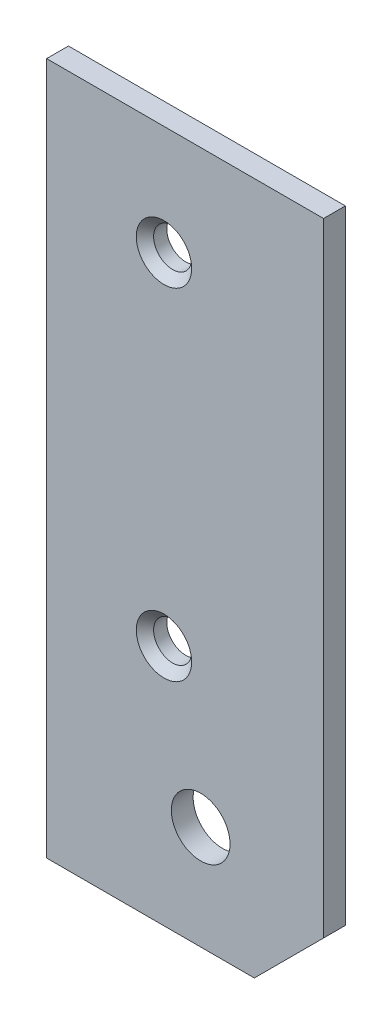
SolidWorks part; units mm, degrees
ref_plane "Front Plane" through (0, 0, 0) normal (0, 0, 1) x (1, 0, 0)
ref_plane "Top Plane" through (0, 0, 0) normal (0, 1, 0) x (1, 0, 0)
ref_plane "Right Plane" through (0, 0, 0) normal (1, 0, 0) x (0, 0, -1)
sketch "Sketch1" plane through (0, 0, 0) normal (0, 0, 1) x (1, 0, 0)
  line L1 (-10.16, -25.4) -> (10.16, -25.4)
  line L2 (-10.16, -25.4) -> (-10.16, 25.4)
  line L3 (-10.16, 25.4) -> (10.16, 25.4)
  line L4 (10.16, -25.4) -> (10.16, 25.4)
  line L5 (-10.16, -25.4) -> (10.16, 25.4) construction
  line L6 (-10.16, 25.4) -> (10.16, -25.4) construction
  point P0 (0, 0)
  dimension "D1" = 20.32
  dimension "D2" = 50.8
extrude "Boss-Extrude1" add sketch "Sketch1" along normal blind 1.6002
chamfer "Chamfer1" distance 5.08 angle 45 1 edges at (10.16, -25.4, 0.8001)
hole_wizard "#3 Clearance Hole1" positions "3DSketch1" profile "Sketch2" hole size "#3" standard "ANSI Inch"
sketch3d "3DSketch1"
  line L0 (-10.16, 25.4, 1.6002) -> (-10.16, -25.4, 1.6002) construction
  line L2 (-10.16, -25.4, 1.6002) -> (5.08, -25.4, 1.6002) construction
  point P0 (-1.5494, -7.62, 1.6002)
  point P10 (-1.5494, 17.38, 1.6002)
  dimension "D1" = 8.6106
  dimension "D2" = 17.78
  dimension "D3" = 25
sketch "Sketch2" plane through (-1.5494, -7.62, 1.6002) normal (1, 0, 0) x (0, -1, 0)
  line L0 (0, 0) -> (0, 12.2694)
  line L1 (0, 12.2694) -> (1.397, 11.43)
  line L2 (1.397, 11.43) -> (1.397, 0.635)
  line L3 (1.397, 0.635) -> (2.032, 0)
  line L5 (2.032, 0) -> (0, 0)
  line L6 (-1.397, 0.635) -> (-2.032, 0) construction
  line L10 (0, 12.2694) -> (-1.397, 11.43) construction
  line L11 (0, -6.35) -> (0, 107.95) construction
  dimension "Hole Dia." = 2.794
  dimension "Hole Depth" = 11.43
  dimension "Near C'Sink Dia." = 4.064
  dimension "Near C'Sink Angle" = 90
  dimension "Drill Angle" = 118
hole_wizard "#8 Clearance Hole1" positions "3DSketch2" profile "Sketch4" hole size "#8" standard "ANSI Inch" end condition through all
sketch3d "3DSketch2"
  line L0 (-10.16, 25.4, 1.6002) -> (-10.16, -25.4, 1.6002) construction
  line L1 (-10.16, -25.4, 1.6002) -> (5.08, -25.4, 1.6002) construction
  point P0 (1.143, -17.78, 1.6002)
  dimension "D1" = 11.303
  dimension "D2" = 7.62
sketch "Sketch4" plane through (1.143, -17.78, 1.6002) normal (1, 0, 0) x (0, -1, 0)
  line L0 (0, 0) -> (0, 1.6002)
  line L1 (0, 1.6002) -> (2.1526, 1.6002)
  line L2 (2.1526, 1.6002) -> (2.1526, 0)
  line L5 (2.1526, 0) -> (0, 0)
  line L11 (0, -6.35) -> (0, 107.95) construction
  dimension "Thru Hole Dia." = 4.3053
  dimension "Thru Hole Depth" = 1.6002
